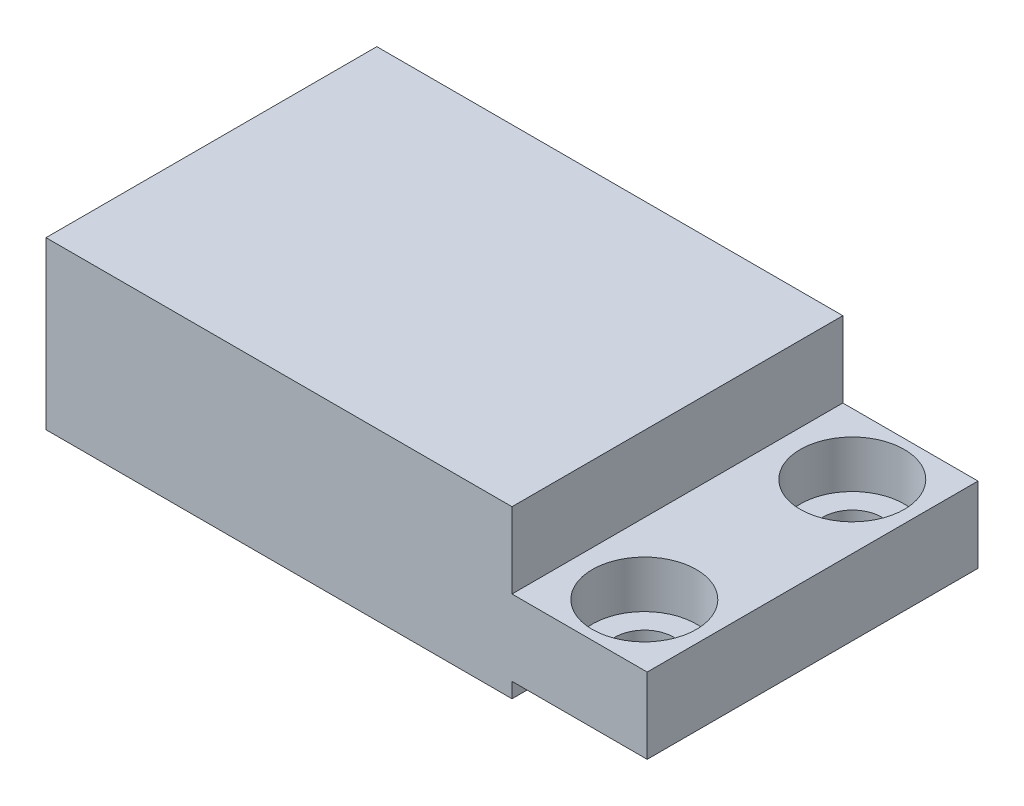
SolidWorks part; units mm, degrees
ref_plane "Płaszczyzna przednia" through (0, 0, 0) normal (0, 0, 1) x (1, 0, 0)
ref_plane "Płaszczyzna górna" through (0, 0, 0) normal (0, 1, 0) x (1, 0, 0)
ref_plane "Płaszczyzna prawa" through (0, 0, 0) normal (1, 0, 0) x (0, 0, -1)
sketch "Szkic1" plane through (0, 0, 0) normal (0, 0, 1) x (1, 0, 0)
  line L1 (-15.9, 0) -> (15.9, 0)
  line L2 (-15.9, 0) -> (-15.9, 8.8)
  line L3 (-15.9, 8.8) -> (15.9, 8.8)
  line L4 (15.9, 0) -> (15.9, 8.8)
  point P4 (0, 0)
  dimension "D1" = 8.8
  dimension "D2" = 31.8
extrude "Dodanie-wyciągnięcie1" add sketch "Szkic1" along normal mid plane 17.5
sketch "Szkic2" plane through (0, 0, 0) normal (0, -1, 0) x (1, 0, 0)
  line L0 (-15.9, -8.75) -> (15.9, -8.75) construction
  line L1 (15.9, 8.75) -> (8.75, 8.75)
  line L2 (15.9, 8.75) -> (15.9, -8.75)
  line L3 (15.9, -8.75) -> (8.75, -8.75)
  line L4 (8.75, 8.75) -> (8.75, -8.75)
  dimension "D1" = 7.15
extrude "Wytnij-wyciągnięcie1" cut sketch "Szkic2" against normal blind 0.8
sketch "Szkic3" plane through (0, 0, 8.75) normal (0, 0, 1) x (1, 0, 0)
  line L0 (15.9, 8.8) -> (-15.9, 8.8) construction
  line L1 (8.75, 8.8) -> (15.9, 8.8)
  line L2 (8.75, 8.8) -> (8.75, 4.8)
  line L3 (8.75, 4.8) -> (15.9, 4.8)
  line L4 (15.9, 8.8) -> (15.9, 4.8)
  line L5 (15.9, 0.8) -> (15.9, 8.8) construction
  line L6 (8.75, 0.8) -> (8.75, 0) construction
  point P10 (0, 0)
  dimension "D1" = 4
extrude "Wytnij-wyciągnięcie2" cut sketch "Szkic3" against normal through all
hole_wizard "Pogłębienie walcowe pod M2.5 Śrubę z łbem walcowym z gniazdem1" positions "Szkic4" profile "Szkic5" counterbore size "M2.5" standard "Ansi Metric" end condition through all
sketch "Szkic4" plane through (0, 4.8, 0) normal (0, 1, 0) x (1, 0, 0)
  line L0 (12.5, 5.5) -> (12.5, -5.5)
  point P0 (12.5, 5.5)
  point P2 (12.5, -5.5)
  dimension "D1" = 12.5
  dimension "D2" = 5.5
  dimension "D3" = 11
sketch "Szkic5" plane through (12.5, 4.8, -5.5) normal (1, 0, 0) x (0, 0, 1)
  line L0 (0, 0) -> (0, 4.8)
  line L1 (0, 4.8) -> (1.55, 4.8)
  line L3 (1.55, 4.8) -> (1.55, 2.5)
  line L4 (1.55, 2.5) -> (2.75, 2.5)
  line L5 (2.75, 2.5) -> (2.75, 0)
  line L7 (2.75, 0) -> (0, 0)
  line L11 (0, -6.35) -> (0, 107.95) construction
  dimension "Średnica otworu na wylot" = 3.1
  dimension "Głębokość otworu na wylot" = 4.8
  dimension "Średnica pogłębienia walcowego" = 5.5
  dimension "Głębokość pogłębienia walcowego" = 2.5
equation "\"D1@Szkic2\"=(31.8-17.5)/2"
